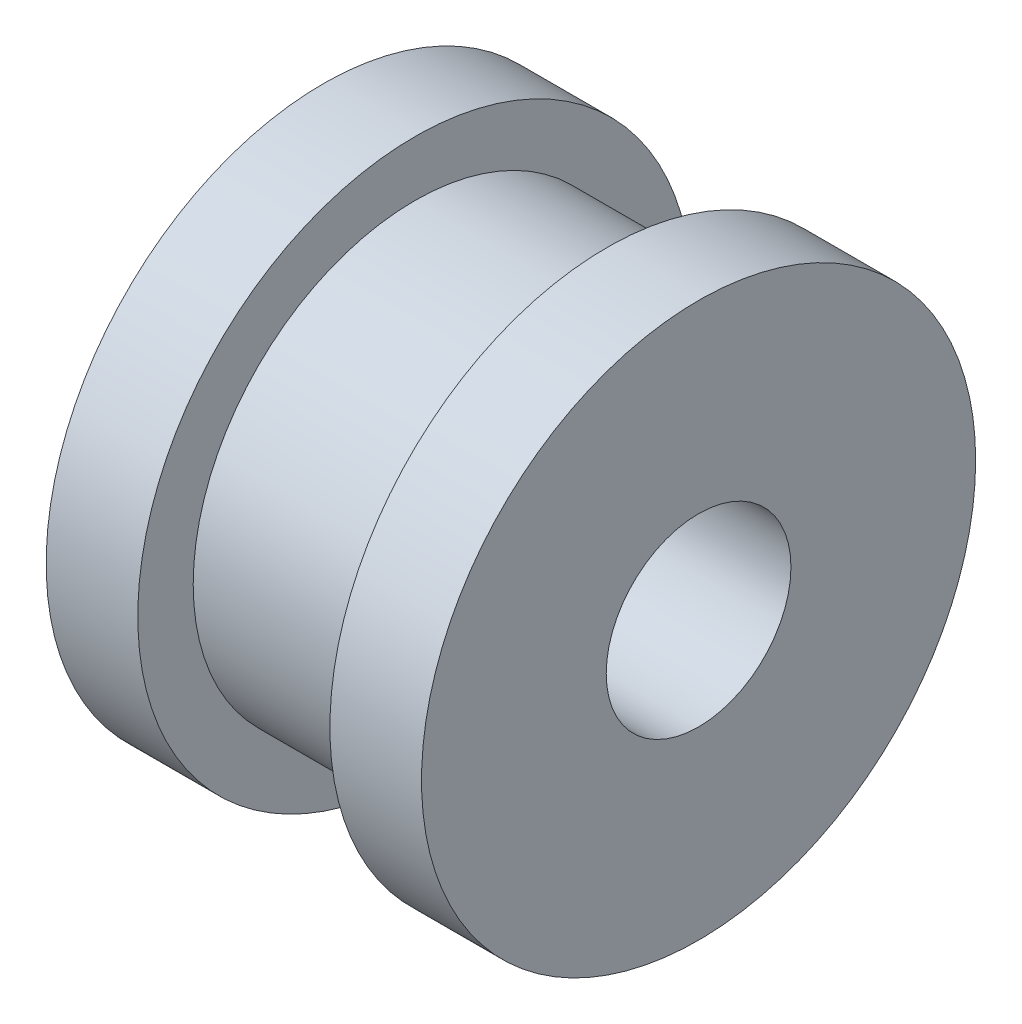
SolidWorks part; units mm, degrees
material "Silicon Rubber"
ref_plane "Front Plane" through (0, 0, 0) normal (0, 0, 1) x (1, 0, 0)
ref_plane "Top Plane" through (0, 0, 0) normal (0, 1, 0) x (1, 0, 0)
ref_plane "Right Plane" through (0, 0, 0) normal (1, 0, 0) x (0, 0, -1)
sketch "Sketch1" plane through (0, 0, 0) normal (1, 0, 0) x (0, 0, -1)
  circle A0 centre (0, 0) radius 3.175
  circle A1 centre (0, 0) radius 9.525
  dimension "D1" = 6.35
  dimension "D2" = 19.05
extrude "Boss-Extrude1" add sketch "Sketch1" along normal blind 3.1496
sketch "Sketch2" plane through (3.1496, 0, 0) normal (1, 0, 0) x (0, 0, -1)
  circle A0 centre (0, 0) radius 3.175
  circle A1 centre (0, 0) radius 7.62
  dimension "D1" = 15.24
extrude "Boss-Extrude2" add sketch "Sketch2" along normal blind 6.604
sketch "Sketch3" plane through (9.7536, 0, 0) normal (1, 0, 0) x (0, 0, -1)
  circle A0 centre (0, 0) radius 3.175
  circle A1 centre (0, 0) radius 9.525
extrude "Boss-Extrude3" add sketch "Sketch3" along normal blind 3.1496
